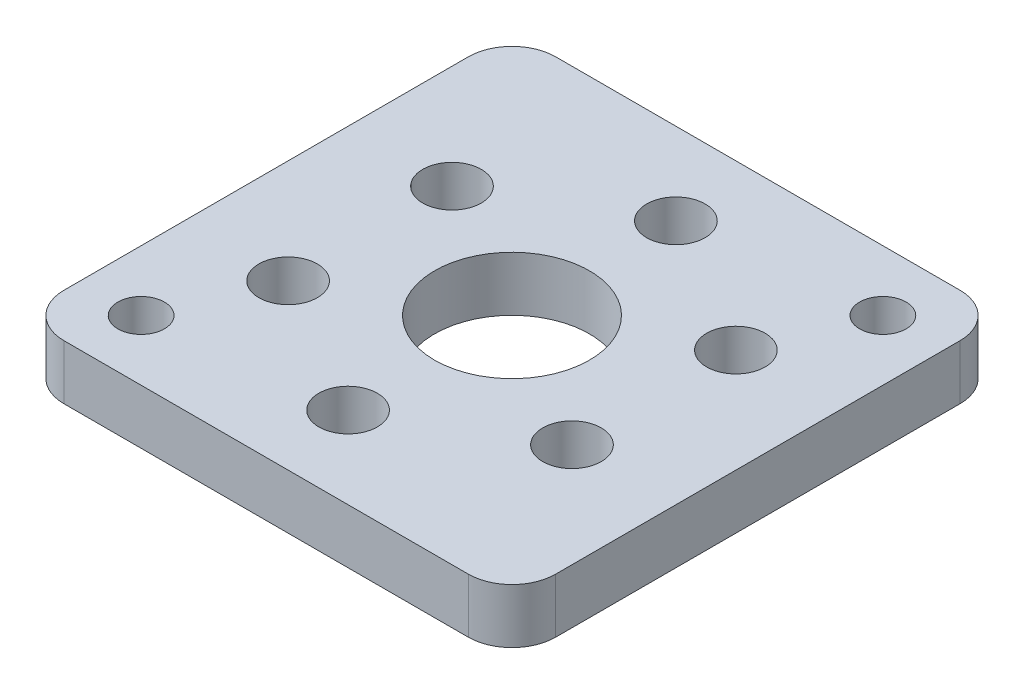
SolidWorks part; units mm, degrees
ref_plane "Front Plane" through (0, 0, 0) normal (0, 0, 1) x (1, 0, 0)
ref_plane "Top Plane" through (0, 0, 0) normal (0, 1, 0) x (1, 0, 0)
ref_plane "Right Plane" through (0, 0, 0) normal (1, 0, 0) x (0, 0, -1)
sketch "Sketch1" plane through (0, 0, 0) normal (0, 1, 0) x (1, 0, 0)
  line L1 (-14.2875, -14.2875) -> (14.2875, -14.2875)
  line L2 (-14.2875, -14.2875) -> (-14.2875, 14.2875)
  line L3 (-14.2875, 14.2875) -> (14.2875, 14.2875)
  line L4 (14.2875, -14.2875) -> (14.2875, 14.2875)
  line L5 (-14.2875, -14.2875) -> (14.2875, 14.2875) construction
  line L6 (-14.2875, 14.2875) -> (14.2875, -14.2875) construction
  point P0 (0, 0)
  dimension "D1" = 28.575
  dimension "D2" = 28.575
extrude "Boss-Extrude1" add sketch "Sketch1" along normal blind 3.175
sketch "Sketch2" plane through (0, 3.175, 0) normal (0, 1, 0) x (1, 0, 0)
  line L0 (0, -55) -> (0, 55) construction
  line L1 (-55, 0) -> (55, 0) construction
  circle A0 centre (0, 0) radius 4.5
  point P4 (0, 9.525)
  dimension "D1" = 9
  dimension "D2" = 9.525
hole_wizard "M3 Clearance Hole1" positions "Sketch3" profile "Sketch4" hole size "M3" standard "ANSI Metric" end condition through all
sketch "Sketch3" plane through (0, 3.175, 0) normal (0, 1, 0) x (1, 0, 0)
  point P0 (0, 9.525)
sketch "Sketch4" plane through (0, 3.175, -9.525) normal (1, 0, 0) x (0, 0, 1)
  line L0 (0, 0) -> (0, 3.175)
  line L1 (0, 3.175) -> (1.7, 3.175)
  line L2 (1.7, 3.175) -> (1.7, 0)
  line L5 (1.7, 0) -> (0, 0)
  line L11 (0, -6.35) -> (0, 107.95) construction
  dimension "Thru Hole Dia." = 3.4
  dimension "Thru Hole Depth" = 3.175
extrude "Cut-Extrude2" cut sketch "Sketch2" against normal through all contours A0
pattern_circular "CirPattern1" count 6 over 360 about axis through (0, 0, 0) along (0, 1, 0) of "M3 Clearance Hole1"
sketch "Sketch5" plane through (0, 3.175, 0) normal (0, 1, 0) x (1, 0, 0)
  line L0 (-1.7463, 0) -> (1.7463, 0) construction
  line L3 (-10.7763, -10.7763) -> (10.7763, 10.7763) construction
  point P10 (-10.7763, -10.7763)
  point P11 (10.7763, 10.7763)
  point P12 (0, 0)
  dimension "D1" = 15.24
  dimension "D2" = 45
hole_wizard "#6-32 Tapped Hole1" positions "Sketch6" profile "Sketch8" tap size "#6-32" standard "ANSI Inch" end condition through all
sketch "Sketch6" plane through (0, 3.175, 0) normal (0, 1, 0) x (1, 0, 0)
  point P0 (10.7763, 10.7763)
  point P3 (-10.7763, -10.7763)
sketch "Sketch8" plane through (10.7763, 3.175, -10.7763) normal (1, 0, 0) x (0, 0, 1)
  line L0 (0, 0) -> (0, 3.175)
  line L1 (0, 3.175) -> (1.3525, 3.175)
  line L2 (1.3525, 3.175) -> (1.3525, 0)
  line L5 (1.3525, 0) -> (0, 0)
  line L11 (0, -6.35) -> (0, 107.95) construction
  dimension "Thru Tap Drill Dia." = 2.7051
  dimension "Thru Tap Drill Depth" = 3.175
cosmetic thread "Hole Thread1" parameters "D2"=3.5052
cosmetic thread "Hole Thread2" parameters "D2"=3.5052
fillet "Fillet1" radius 2.54 4 edges at (14.2875, 1.5875, -14.2875) (14.2875, 1.5875, 14.2875) (-14.2875, 1.5875, -14.2875) (-14.2875, 1.5875, 14.2875)
ref_plane "Plane1" through (0, 0, 0) normal (-0.7071, 0, -0.7071) x (-0.7071, 0, 0.7071)
